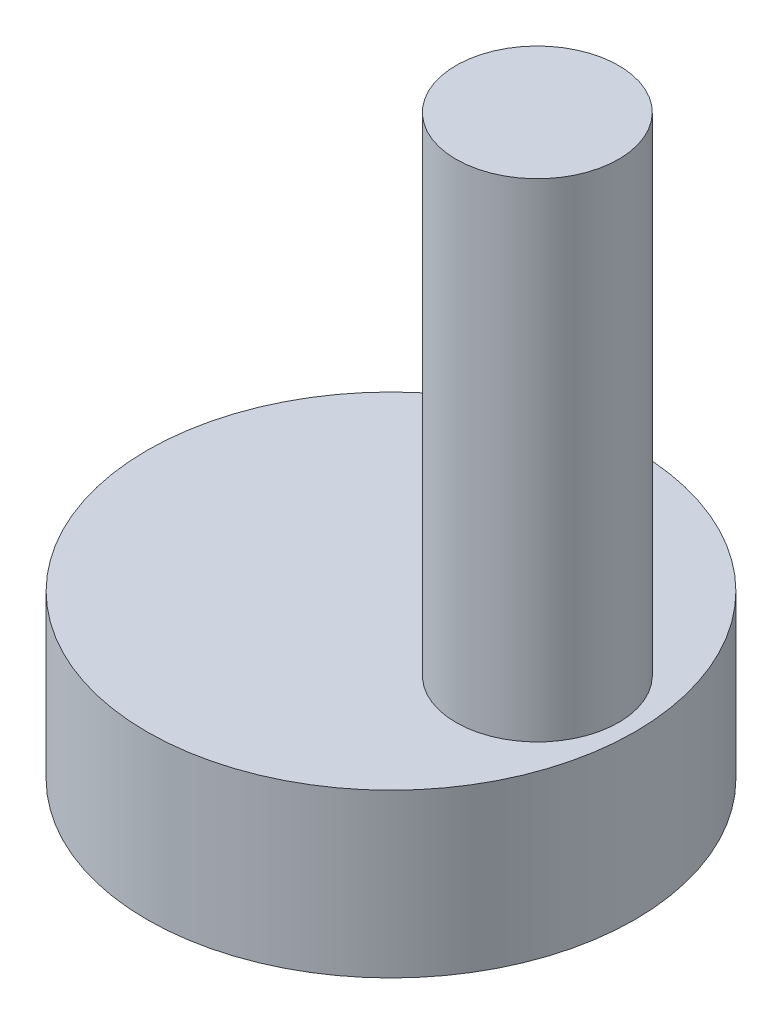
SolidWorks part; units mm, degrees
ref_plane "Front Plane" through (0, 0, 0) normal (0, 0, 1) x (1, 0, 0)
ref_plane "Top Plane" through (0, 0, 0) normal (0, 1, 0) x (1, 0, 0)
ref_plane "Right Plane" through (0, 0, 0) normal (1, 0, 0) x (0, 0, -1)
sketch "Sketch1" plane through (0, 0, 0) normal (0, 1, 0) x (1, 0, 0)
  circle A0 centre (0, 0) radius 15
  dimension "D1" = 30
extrude "Boss-Extrude1" add sketch "Sketch1" along normal blind 10
sketch "Sketch2" plane through (0, 10, 0) normal (0, 1, 0) x (1, 0, 0)
  circle A0 centre (9, 0) radius 5
  dimension "D1" = 10
  dimension "D2" = 9
extrude "Boss-Extrude2" add sketch "Sketch2" along normal blind 30
